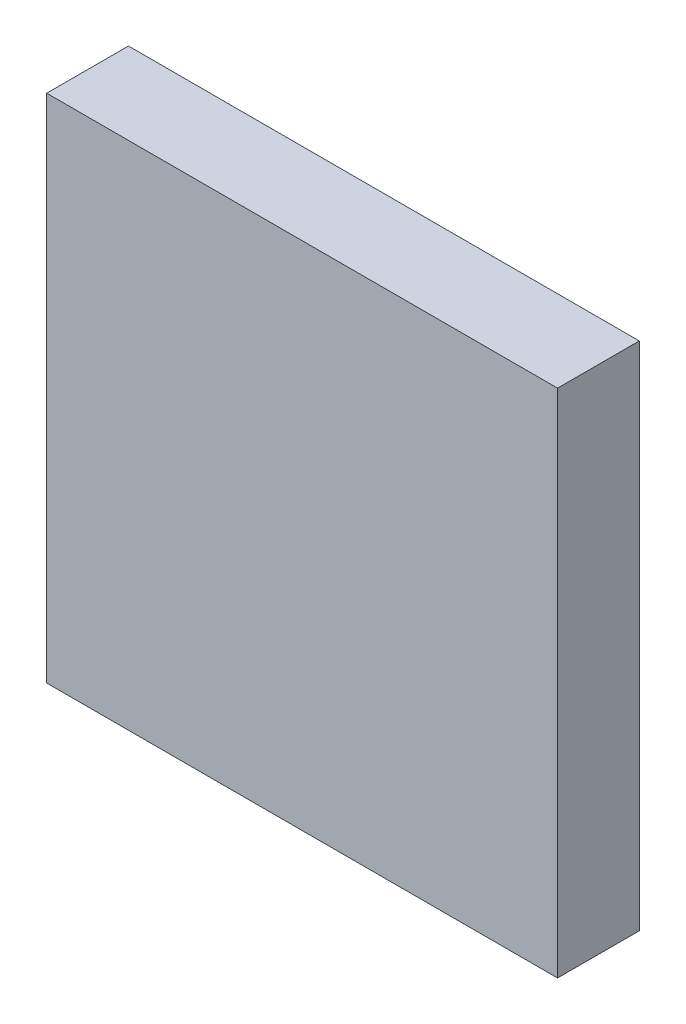
SolidWorks part; units mm, degrees
ref_plane "Front Plane" through (0, 0, 0) normal (0, 0, 1) x (1, 0, 0)
ref_plane "Top Plane" through (0, 0, 0) normal (0, 1, 0) x (1, 0, 0)
ref_plane "Right Plane" through (0, 0, 0) normal (1, 0, 0) x (0, 0, -1)
sketch "Sketch1" plane through (0, 0, 0) normal (0, 0, 1) x (1, 0, 0)
  line L1 (0, 0) -> (25, 0)
  line L2 (0, 0) -> (0, 25)
  line L3 (0, 25) -> (25, 25)
  line L4 (25, 0) -> (25, 25)
  dimension "D1" = 25
  dimension "D2" = 25
extrude "Boss-Extrude1" add sketch "Sketch1" along normal blind 4
